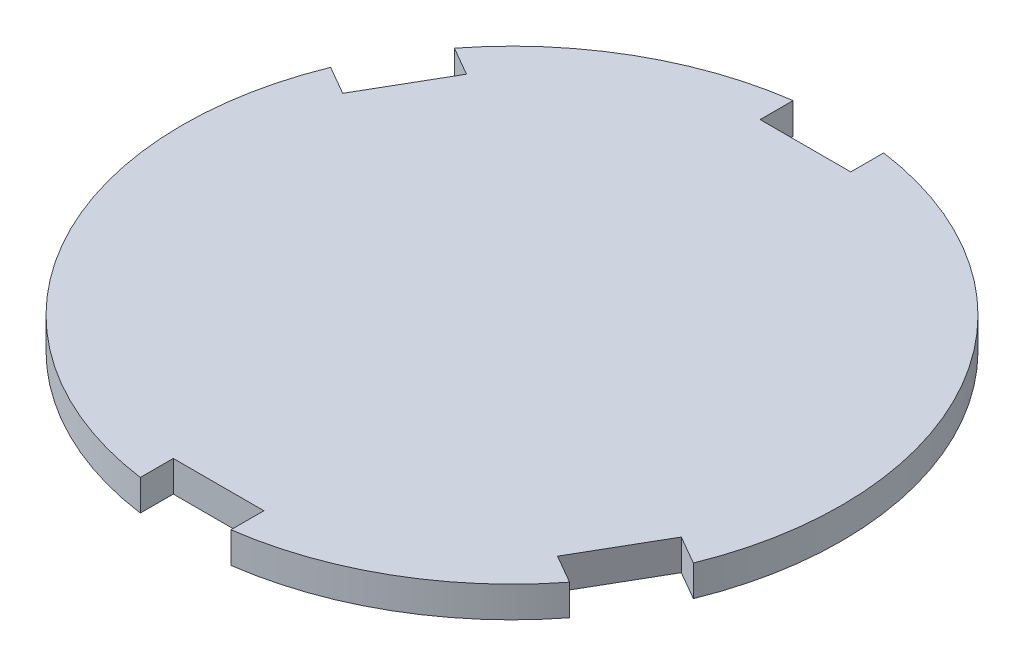
SolidWorks part; units mm, degrees
material "6061-T6 (SS)"
ref_plane "Front Plane" through (0, 0, 0) normal (0, 0, 1) x (1, 0, 0)
ref_plane "Top Plane" through (0, 0, 0) normal (0, 1, 0) x (1, 0, 0)
ref_plane "Right Plane" through (0, 0, 0) normal (1, 0, 0) x (0, 0, -1)
sketch "Sketch1" plane through (0, 0, 0) normal (0, 1, 0) x (1, 0, 0)
  circle A0 centre (0, 0) radius 50.8
  dimension "D1" = 101.6
extrude "Boss-Extrude1" add sketch "Sketch1" along normal blind 4.7625
sketch "Sketch2" plane through (0, 4.7625, 0) normal (0, 1, 0) x (1, 0, 0)
  line L0 (0, 0) -> (0, -55.8813) construction
  line L1 (0, 0) -> (59.2491, 0) construction
  line L2 (-6.985, -45.2375) -> (6.985, -45.2375)
  line L3 (6.985, -45.2375) -> (6.985, -50.3175)
  line L4 (-6.985, -45.2375) -> (-6.985, -50.3175)
  line L5 (-6.985, 45.2375) -> (-6.985, 50.3175)
  line L6 (-6.985, 45.2375) -> (6.985, 45.2375)
  line L7 (6.985, 45.2375) -> (6.985, 50.3175)
  circle A0 centre (0, 0) radius 50.8 construction
  arc A1 (-6.985, -50.3175) -> (6.985, -50.3175) centre (0, 0) ccw
  arc A2 (-6.985, 50.3175) -> (6.985, 50.3175) centre (0, 0) cw
  point P7 (0, -45.2375)
  dimension "D1" = 13.97
  dimension "D2" = 5.08
extrude "Cut-Extrude1" cut sketch "Sketch2" against normal up to next
sketch "Sketch3" plane through (0, 4.7625, 0) normal (0, 1, 0) x (1, 0, 0)
  line L0 (0, 0) -> (49.3026, -28.4649) construction
  line L1 (0, 0) -> (26.5906, 46.0563) construction
  line L2 (0, -55) -> (0, 55) construction
  line L3 (35.6843, -28.6679) -> (42.6693, -16.5696)
  line L4 (35.6843, -28.6679) -> (40.0837, -31.2079)
  line L5 (42.6693, -16.5696) -> (47.0687, -19.1096)
  line L6 (-35.6843, 28.6679) -> (-40.0837, 31.2079)
  line L7 (-42.6693, 16.5696) -> (-35.6843, 28.6679)
  line L8 (-42.6693, 16.5696) -> (-47.0687, 19.1096)
  arc A0 (6.985, -50.3175) -> (6.985, 50.3175) centre (0, 0) ccw construction
  arc A1 (47.0687, -19.1096) -> (40.0837, -31.2079) centre (0, 0) cw
  arc A2 (-40.0837, 31.2079) -> (-47.0687, 19.1096) centre (0, 0) ccw
  point P7 (39.1768, -22.6187)
  dimension "D1" = 60
  dimension "D2" = 13.97
  dimension "D3" = 5.08
extrude "Cut-Extrude2" cut sketch "Sketch3" against normal up to next
equation "\"b\"=4"
equation "\"D1@Sketch1\"=\"b\""
